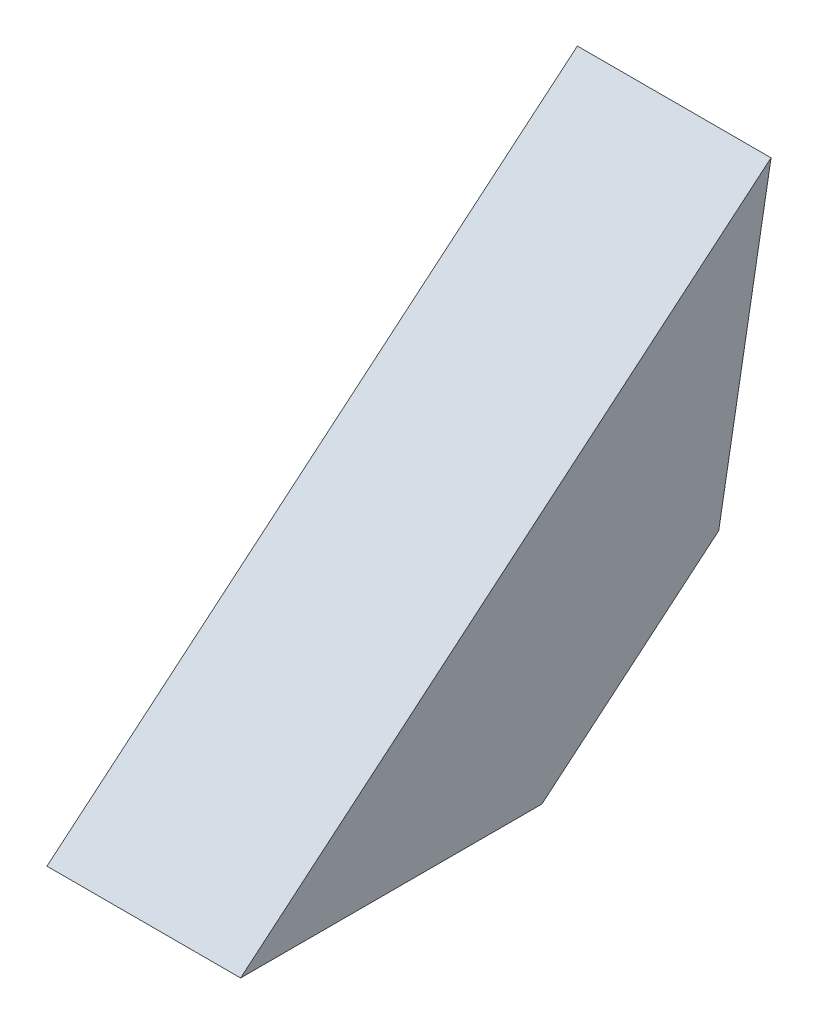
SolidWorks part; units mm, degrees
ref_plane "Front Plane" through (0, 0, 0) normal (0, 0, 1) x (1, 0, 0)
ref_plane "Top Plane" through (0, 0, 0) normal (0, 1, 0) x (1, 0, 0)
ref_plane "Right Plane" through (0, 0, 0) normal (1, 0, 0) x (0, 0, -1)
sketch "Sketch1" plane through (0, 0, 0) normal (1, 0, 0) x (0, 0, -1)
  line L2 (-15.5572, 0) -> (0, 0)
  line L3 (0, 0) -> (9.1294, 7.6604)
  line L4 (9.1294, 7.6604) -> (11.8308, 22.9813)
  line L5 (11.8308, 22.9813) -> (-15.5572, 0)
  line L6 (9.1294, 7.6604) -> (7.7786, 0) construction
  line L7 (7.7786, 0) -> (0, 0) construction
  dimension "D1" = 100
  dimension "D2" = 100
  dimension "D3" = 5
  dimension "D4" = 10
extrude "Boss-Extrude1" add sketch "Sketch1" along normal blind 10
equation "\"D2@Sketch1\"=\"D1@Sketch1\""
